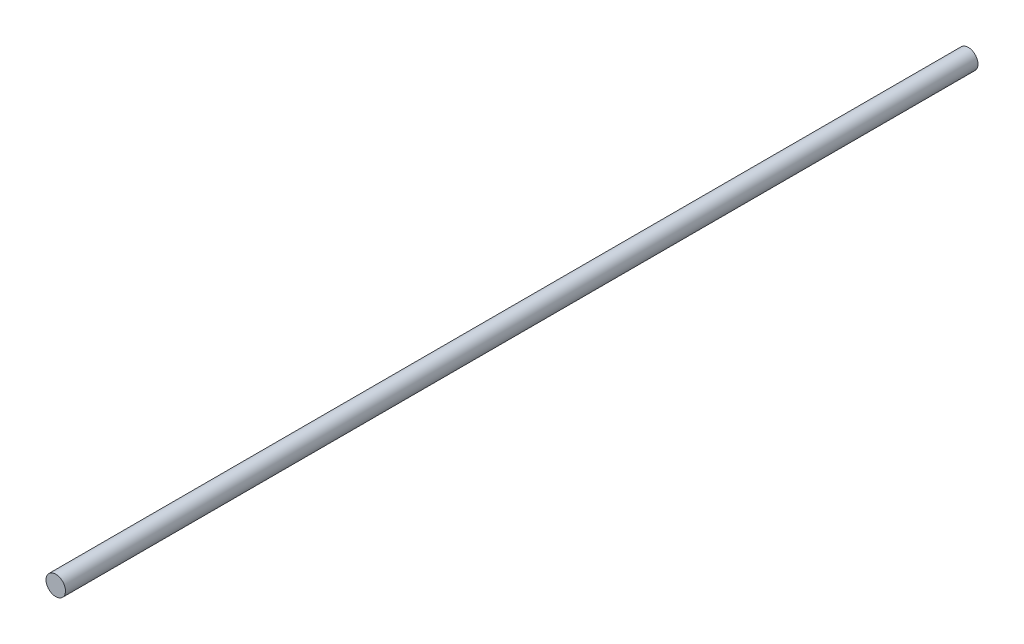
SolidWorks part; units mm, degrees
ref_plane "Alzado" through (0, 0, 0) normal (0, 0, 1) x (1, 0, 0)
ref_plane "Planta" through (0, 0, 0) normal (0, 1, 0) x (1, 0, 0)
ref_plane "Vista lateral" through (0, 0, 0) normal (1, 0, 0) x (0, 0, -1)
sketch "Croquis1" plane through (0, 0, 0) normal (0, 0, 1) x (1, 0, 0)
  circle A0 centre (0, 0) radius 4.5
  dimension "D1" = 9
extrude "Saliente-Extruir1" add sketch "Croquis1" along normal blind 421.64
